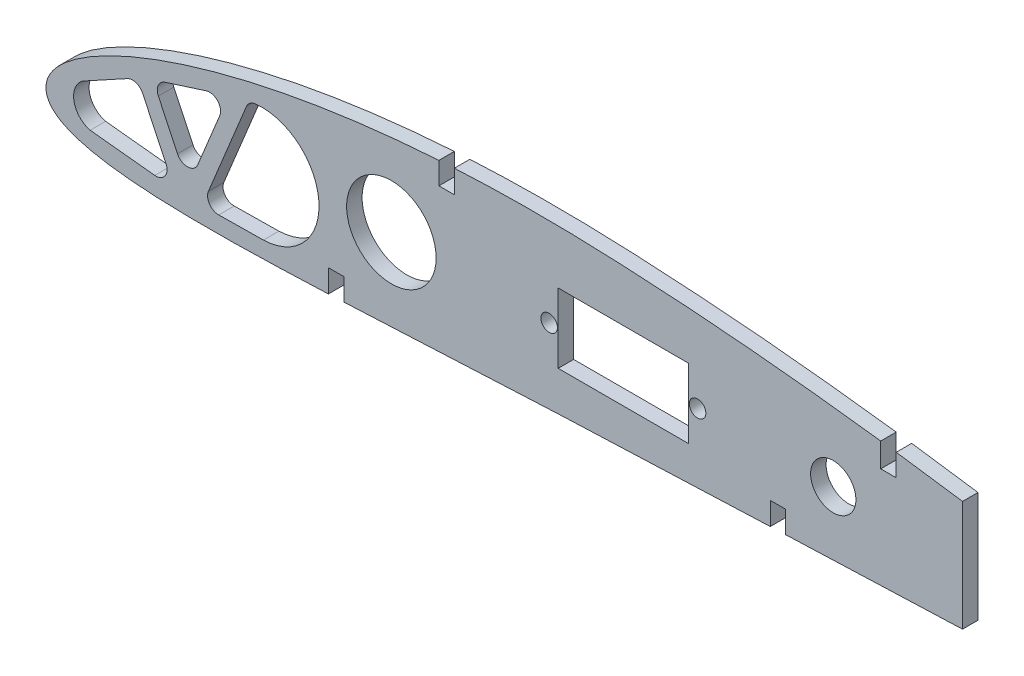
SolidWorks part; units mm, degrees
material "фанера"
ref_plane "Front" through (0, 0, 0) normal (0, 0, 1) x (1, 0, 0)
ref_plane "Top" through (0, 0, 0) normal (0, 1, 0) x (1, 0, 0)
ref_plane "Right" through (0, 0, 0) normal (1, 0, 0) x (0, 0, -1)
curve "Кривая1"
  spline degree 3 poles (0.048, 0.6214, 0) (0.0227, 0.3735, 0) (-0.0278, -0.1225, 0) (0.078, -0.8844, 0) (0.3497, -1.6388, 0) (0.8143, -2.3651, 0) (1.4635, -3.0393, 0) (2.291, -3.661, 0) (3.3059, -4.2358, 0) (4.5353, -4.7737, 0) (6.0297, -5.2822, 0) (7.869, -5.7653, 0) (10.1688, -6.2217, 0) (13.0754, -6.6396, 0) (16.7281, -6.993, 0) (21.19, -7.2473, 0) (26.4, -7.3766, 0) (32.1974, -7.3763, 0) (38.3978, -7.2614, 0) (44.8576, -7.0566, 0) (51.4865, -6.7865, 0) (58.231, -6.4723, 0) (65.0521, -6.1329, 0) (71.9108, -5.784, 0) (78.7714, -5.4397, 0) (85.6105, -5.111, 0) (92.4321, -4.805, 0) (99.255, -4.532, 0) (106.0974, -4.2783, 0) (112.9692, -4.0031, 0) (119.8644, -3.7232, 0) (126.7739, -3.4401, 0) (133.6816, -3.1587, 0) (140.5819, -2.8824, 0) (147.472, -2.6139, 0) (154.3526, -2.3556, 0) (161.225, -2.1094, 0) (168.0909, -1.8766, 0) (174.9516, -1.6586, 0) (181.8086, -1.4564, 0) (188.6632, -1.2704, 0) (195.5166, -1.1011, 0) (202.3695, -0.9486, 0) (209.2212, -0.8129, 0) (216.0668, -0.6936, 0) (222.8864, -0.5903, 0) (229.6176, -0.5029, 0) (236.0874, -0.4315, 0) (241.9808, -0.3765, 0) (246.559, -0.3395, 0) (249.1205, -0.3213, 0) (250, -0.315, 0) knots 0 0 0 0 0.002941 0.005884 0.009016 0.012365 0.016008 0.020037 0.024574 0.029784 0.035897 0.04324 0.052276 0.063635 0.077983 0.095698 0.11652 0.139661 0.164312 0.189919 0.216157 0.242838 0.269834 0.296993 0.324123 0.351139 0.378036 0.404946 0.431961 0.459078 0.486347 0.513641 0.540929 0.568176 0.59538 0.622543 0.649673 0.676775 0.703855 0.730919 0.757971 0.785018 0.812062 0.839103 0.866132 0.893099 0.919831 0.94581 0.969681 0.98959 1 1 1 1
curve "Кривая2"
  spline degree 3 poles (250, 0.315, 0) (249.1557, 0.545, 0) (246.7202, 1.2085, 0) (242.3913, 2.3583, 0) (236.8498, 3.7876, 0) (230.7799, 5.298, 0) (224.4559, 6.8129, 0) (218.0305, 8.2916, 0) (211.5624, 9.7197, 0) (205.0724, 11.0924, 0) (198.568, 12.4079, 0) (192.0524, 13.6653, 0) (185.5276, 14.8641, 0) (178.9953, 16.0034, 0) (172.4571, 17.0824, 0) (165.9143, 18.0998, 0) (159.3687, 19.0545, 0) (152.8218, 19.9449, 0) (146.2754, 20.7693, 0) (139.7314, 21.5257, 0) (133.1918, 22.212, 0) (126.6587, 22.8257, 0) (120.1368, 23.364, 0) (113.6286, 23.8247, 0) (107.1527, 24.2002, 0) (100.7411, 24.4984, 0) (94.4118, 24.6866, 0) (88.1559, 24.7401, 0) (81.949, 24.6588, 0) (75.7805, 24.441, 0) (69.6537, 24.0819, 0) (63.5754, 23.578, 0) (57.5552, 22.9249, 0) (51.6058, 22.1191, 0) (45.7444, 21.1566, 0) (39.9959, 20.0354, 0) (34.3979, 18.7563, 0) (29.0104, 17.3276, 0) (23.9258, 15.7719, 0) (19.2707, 14.1343, 0) (15.1791, 12.4833, 0) (11.7405, 10.8956, 0) (8.9594, 9.4296, 0) (6.7609, 8.1086, 0) (5.0337, 6.9246, 0) (3.6717, 5.8542, 0) (2.5921, 4.8713, 0) (1.7382, 3.9526, 0) (1.0699, 3.0809, 0) (0.5716, 2.2416, 0) (0.2158, 1.4308, 0) (0.1023, 0.8832, 0) (0.048, 0.6214, 0) knots 0 0 0 0 0.010162 0.029313 0.052012 0.076619 0.101948 0.127526 0.153184 0.178868 0.204558 0.230246 0.255926 0.281594 0.307246 0.332878 0.358485 0.384061 0.409603 0.435104 0.460559 0.485959 0.511303 0.536552 0.561723 0.586629 0.611085 0.635251 0.659272 0.683164 0.706922 0.730536 0.753983 0.777235 0.800246 0.822951 0.845237 0.866916 0.887662 0.906968 0.924203 0.938879 0.950932 0.960693 0.968647 0.975233 0.980795 0.985584 0.989782 0.993521 0.996902 1 1 1 1
sketch "Эскиз2" plane through (0, 0, 0) normal (0, 0, 1) x (1, 0, 0)
  line L0 (-1.2592, 0) -> (250.7702, 0) construction
  line L1 (250.1305, 0) -> (250.1305, 80.0888) construction
  line L2 (0, 0) -> (0, 69.7453) construction
  line L3 (62.5326, 123.1249) -> (62.5326, -48.5934) construction
  line L4 (142.5326, 131.1199) -> (142.5326, -55.0117) construction
  line L5 (62.5326, 8.5923) -> (142.5326, 8.6947) construction
  line L6 (62.5326, 8.5923) -> (150.6431, 8.5923) construction
  line L7 (175.0913, 92.567) -> (175.0913, -39.4544) construction
  line L8 (165.9405, 18.0854) -> (165.9405, -1.9504)
  line L18 (17.4887, 7.868) -> (21.7254, -1.0733)
  line L19 (29.4016, -1.5679) -> (36.2887, 15.1777)
  line L20 (20.3422, 8.8519) -> (23.813, 1.5271)
  line L21 (27.4701, 1.6228) -> (31.461, 11.3265)
  line L22 (7.9994, -2.6904) -> (19.7094, -3.9188)
  line L23 (31.2779, -4.3285) -> (39.3668, -4.221)
  line L24 (6.5801, 4.311) -> (14.7212, 8.7661)
  line L25 (21.5421, 11.6138) -> (29.0038, 13.9928)
  line L26 (72.5326, 27.406) -> (72.5326, 20.4403) construction
  line L27 (52.5326, -12.1202) -> (52.5326, -2.6904) construction
  line L28 (152.5326, 24.4982) -> (152.5326, 15.921) construction
  line L29 (132.5326, -7.5811) -> (132.5326, 3.1811) construction
  line L30 (151.1326, 20.1529) -> (151.1326, 15.7875)
  line L31 (151.1326, 15.7875) -> (153.9326, 15.7875)
  line L32 (153.9326, 15.7875) -> (153.9326, 19.7875)
  line L33 (131.1326, -3.2627) -> (131.1326, 0.8506)
  line L34 (131.1326, 0.8506) -> (133.9326, 0.8506)
  line L35 (133.9326, 0.8506) -> (133.9326, -3.1494)
  line L36 (71.1326, 24.1575) -> (71.1326, 20.1575)
  line L37 (71.1326, 20.1575) -> (73.9326, 20.1575)
  line L38 (73.9326, 20.1575) -> (73.9326, 24.3239)
  line L39 (51.1326, -6.7954) -> (51.1326, -2.6707)
  line L40 (51.1326, -2.6707) -> (53.9326, -2.6707)
  line L41 (53.9326, -2.6707) -> (53.9326, -6.6707)
  line L42 (116.3326, 14.946) -> (119.6026, 14.946) construction
  line L43 (92.7326, 2.346) -> (116.3326, 2.346)
  line L44 (92.7326, 2.346) -> (92.7326, 14.946)
  line L45 (92.7326, 14.946) -> (116.3326, 14.946)
  line L46 (116.3326, 2.346) -> (116.3326, 14.946)
  line L47 (92.7326, 2.346) -> (116.3326, 14.946) construction
  line L48 (92.7326, 14.946) -> (116.3326, 2.346) construction
  line L49 (119.6026, 14.946) -> (119.6026, 2.346) construction
  line L50 (119.6026, 2.346) -> (116.3326, 2.346) construction
  line L51 (104.5326, 11.3265) -> (104.5326, 5.8512) construction
  arc A0 (250, 0.315) -> (250, -0.315) centre (249.685, 0) cw
  circle A3 centre (62.5326, 8.5923) radius 8.1
  circle A5 centre (62.5326, 8.5923) radius 80 construction
  circle A6 centre (142.5326, 8.6947) radius 4.1
  arc A7 (175.0913, 16.6448) -> (175.0913, -1.657) centre (175.0913, 7.4939) ccw
  arc A16 (37.9117, 16.4041) -> (36.2887, 15.1777) centre (38.1384, 14.417) ccw
  arc A20 (6.5801, 4.311) -> (7.9994, -2.6904) centre (8.9558, 1.1481) ccw
  arc A21 (37.9117, 16.4041) -> (39.3668, -4.221) centre (39.0848, 6.123) cw
  arc A22 (23.813, 1.5271) -> (27.4701, 1.6228) centre (25.6204, 2.3835) ccw
  arc A23 (31.461, 11.3265) -> (29.0038, 13.9928) centre (29.6113, 12.0873) ccw
  arc A24 (20.3422, 8.8519) -> (21.5421, 11.6138) centre (22.1496, 9.7083) cw
  arc A25 (17.4887, 7.868) -> (14.7212, 8.7661) centre (15.6813, 7.0116) ccw
  arc A26 (19.7094, -3.9188) -> (21.7254, -1.0733) centre (19.9181, -1.9297) ccw
  arc A27 (29.4016, -1.5679) -> (31.2779, -4.3285) centre (31.2513, -2.3286) ccw
  circle A28 centre (175.0913, 7.4939) radius 1
  circle A29 centre (117.9676, 8.6632) radius 1.5
  circle A30 centre (91.0976, 8.6632) radius 1.5
  spline S0 degree 3 poles (250, 0.315) (249.1557, 0.545) (246.7202, 1.2085) (242.3913, 2.3583) (236.8498, 3.7876) (230.7799, 5.298) (224.4559, 6.8129) (218.0305, 8.2916) (211.5624, 9.7197) (205.0724, 11.0924) (198.568, 12.4079) (192.0524, 13.6653) (185.5276, 14.8641) (178.9953, 16.0034) (172.4571, 17.0824) (165.9143, 18.0998) (159.3687, 19.0545) (152.8218, 19.9449) (146.2754, 20.7693) (139.7314, 21.5257) (133.1918, 22.212) (126.6587, 22.8257) (120.1368, 23.364) (113.6286, 23.8247) (107.1527, 24.2002) (100.7411, 24.4984) (94.4118, 24.6866) (88.1559, 24.7401) (81.949, 24.6588) (75.7805, 24.441) (69.6537, 24.0819) (63.5754, 23.578) (57.5552, 22.9249) (51.6058, 22.1191) (45.7444, 21.1566) (39.9959, 20.0354) (34.3979, 18.7563) (29.0104, 17.3276) (23.9258, 15.7719) (19.2707, 14.1343) (15.1791, 12.4833) (11.7405, 10.8956) (8.9594, 9.4296) (6.7609, 8.1086) (5.0337, 6.9246) (3.6717, 5.8542) (2.5921, 4.8713) (1.7382, 3.9526) (1.0699, 3.0809) (0.5716, 2.2416) (0.2158, 1.4308) (0.1023, 0.8832) (0.048, 0.6214) knots 0 0 0 0 0.010162 0.029313 0.052012 0.076619 0.101948 0.127526 0.153184 0.178868 0.204558 0.230246 0.255926 0.281594 0.307246 0.332878 0.358485 0.384061 0.409603 0.435104 0.460559 0.485959 0.511303 0.536552 0.561723 0.586629 0.611085 0.635251 0.659272 0.683164 0.706922 0.730536 0.753983 0.777235 0.800246 0.822951 0.845237 0.866916 0.887662 0.906968 0.924203 0.938879 0.950932 0.960693 0.968647 0.975233 0.980795 0.985584 0.989782 0.993521 0.996902 1 1 1 1 construction
  spline S1 degree 3 poles (0.048, 0.6214) (0.0227, 0.3735) (-0.0278, -0.1225) (0.078, -0.8844) (0.3497, -1.6388) (0.8143, -2.3651) (1.4635, -3.0393) (2.291, -3.661) (3.3059, -4.2358) (4.5353, -4.7737) (6.0297, -5.2822) (7.869, -5.7653) (10.1688, -6.2217) (13.0754, -6.6396) (16.7281, -6.993) (21.19, -7.2473) (26.4, -7.3766) (32.1974, -7.3763) (38.3978, -7.2614) (44.8576, -7.0566) (51.4865, -6.7865) (58.231, -6.4723) (65.0521, -6.1329) (71.9108, -5.784) (78.7714, -5.4397) (85.6105, -5.111) (92.4321, -4.805) (99.255, -4.532) (106.0974, -4.2783) (112.9692, -4.0031) (119.8644, -3.7232) (126.7739, -3.4401) (133.6816, -3.1587) (140.5819, -2.8824) (147.472, -2.6139) (154.3526, -2.3556) (161.225, -2.1094) (168.0909, -1.8766) (174.9516, -1.6586) (181.8086, -1.4564) (188.6632, -1.2704) (195.5166, -1.1011) (202.3695, -0.9486) (211.4992, -0.7677) (220.6031, -0.6199) (229.6176, -0.5029) (236.0874, -0.4315) (241.9808, -0.3765) (246.559, -0.3395) (249.1205, -0.3213) (250, -0.315) knots 0 0 0 0 0.002941 0.005884 0.009016 0.012365 0.016008 0.020037 0.024574 0.029784 0.035897 0.04324 0.052276 0.063635 0.077983 0.095698 0.11652 0.139661 0.164312 0.189919 0.216157 0.242838 0.269834 0.296993 0.324123 0.351139 0.378036 0.404946 0.431961 0.459078 0.486347 0.513641 0.540929 0.568176 0.59538 0.622543 0.649673 0.676775 0.703855 0.730919 0.757971 0.785018 0.812062 0.839103 0.893099 0.919831 0.94581 0.969681 0.98959 1 1 1 1 construction
  spline S2 degree 3 poles (250, 0.315) (249.1557, 0.545) (246.7202, 1.2085) (242.3913, 2.3583) (236.8498, 3.7876) (230.7799, 5.298) (224.4559, 6.8129) (218.0305, 8.2916) (211.5624, 9.7197) (205.0724, 11.0924) (198.568, 12.4079) (192.0524, 13.6653) (185.5276, 14.8641) (178.9953, 16.0034) (172.4571, 17.0824) (165.9143, 18.0998) (159.7397, 19.0004) (155.7443, 19.5471) (153.9326, 19.7875) knots 0 0 0 0 0.010162 0.029313 0.052012 0.076619 0.101948 0.127526 0.153184 0.178868 0.204558 0.230246 0.255926 0.281594 0.307246 0.332878 0.358485 0.379707 0.379707 0.379707 0.379707
  spline S3 degree 3 poles (0.048, 0.6214) (0.0227, 0.3735) (-0.0278, -0.1225) (0.078, -0.8844) (0.3497, -1.6388) (0.8143, -2.3651) (1.4635, -3.0393) (2.291, -3.661) (3.3059, -4.2358) (4.5353, -4.7737) (6.0297, -5.2822) (7.869, -5.7653) (10.1688, -6.2217) (13.0754, -6.6396) (16.7281, -6.993) (21.19, -7.2473) (26.4, -7.3766) (32.1974, -7.3763) (38.3978, -7.2614) (44.7521, -7.06) (49.0233, -6.8868) (51.1326, -6.7954) knots 0 0 0 0 0.002941 0.005884 0.009016 0.012365 0.016008 0.020037 0.024574 0.029784 0.035897 0.04324 0.052276 0.063635 0.077983 0.095698 0.11652 0.139661 0.164312 0.189919 0.214908 0.214908 0.214908 0.214908
  spline S4 degree 3 poles (151.1326, 20.1529) (149.5127, 20.3609) (145.7129, 20.8343) (139.7314, 21.5257) (133.1918, 22.212) (126.6587, 22.8257) (120.1368, 23.364) (113.6286, 23.8247) (107.1527, 24.2002) (100.7411, 24.4984) (94.4118, 24.6866) (88.1559, 24.7401) (81.949, 24.6588) (77.2124, 24.4916) (74.545, 24.3569) (73.9326, 24.3239) knots 0.390637 0.390637 0.390637 0.390637 0.409603 0.435104 0.460559 0.485959 0.511303 0.536552 0.561723 0.586629 0.611085 0.635251 0.659272 0.683164 0.690286 0.690286 0.690286 0.690286
  spline S5 degree 3 poles (133.9326, -3.1494) (136.1503, -3.0598) (140.6644, -2.8792) (147.472, -2.6139) (154.3526, -2.3556) (161.225, -2.1094) (168.0909, -1.8766) (174.9516, -1.6586) (181.8086, -1.4564) (188.6632, -1.2704) (195.5166, -1.1011) (202.3695, -0.9486) (211.4992, -0.7677) (220.6031, -0.6199) (229.6176, -0.5029) (236.0874, -0.4315) (241.9808, -0.3765) (246.559, -0.3395) (249.1205, -0.3213) (250, -0.315) knots 0.541906 0.541906 0.541906 0.541906 0.568176 0.59538 0.622543 0.649673 0.676775 0.703855 0.730919 0.757971 0.785018 0.812062 0.839103 0.893099 0.919831 0.94581 0.969681 0.98959 1 1 1 1
  spline S6 degree 3 poles (71.1326, 24.1575) (70.636, 24.1252) (68.1106, 23.954) (63.5754, 23.578) (57.5552, 22.9249) (51.6058, 22.1191) (45.7444, 21.1566) (39.9959, 20.0354) (34.3979, 18.7563) (29.0104, 17.3276) (23.9258, 15.7719) (19.2707, 14.1343) (15.1791, 12.4833) (11.7405, 10.8956) (8.9594, 9.4296) (6.7609, 8.1086) (5.0337, 6.9246) (3.6717, 5.8542) (2.5921, 4.8713) (1.7382, 3.9526) (1.0699, 3.0809) (0.5716, 2.2416) (0.2158, 1.4308) (0.1023, 0.8832) (0.048, 0.6214) knots 0.701143 0.701143 0.701143 0.701143 0.706922 0.730536 0.753983 0.777235 0.800246 0.822951 0.845237 0.866916 0.887662 0.906968 0.924203 0.938879 0.950932 0.960693 0.968647 0.975233 0.980795 0.985584 0.989782 0.993521 0.996902 1 1 1 1
  spline S7 degree 3 poles (53.9326, -6.6707) (55.3566, -6.6057) (59.0587, -6.4311) (65.0521, -6.1329) (71.9108, -5.784) (78.7714, -5.4397) (85.6105, -5.111) (92.4321, -4.805) (99.255, -4.532) (106.0974, -4.2783) (112.9692, -4.0031) (119.8644, -3.7232) (125.9231, -3.4749) (129.6799, -3.3217) (131.1326, -3.2627) knots 0.225966 0.225966 0.225966 0.225966 0.242838 0.269834 0.296993 0.324123 0.351139 0.378036 0.404946 0.431961 0.459078 0.486347 0.513641 0.53085 0.53085 0.53085 0.53085
  point P15 (62.5326, 0)
  point P16 (142.5326, 0)
  point P22 (62.5326, -6.2577)
  point P26 (175.0913, 16.6448)
  point P28 (175.0913, -1.657)
  point P34 (104.5326, 8.646)
  point P48 (117.9676, 14.946)
  point P50 (62.5326, 23.4501)
  point P86 (25.7497, -2.5601)
  point P88 (23.2497, -4.2901)
  point P91 (28.2497, -4.3687)
  dimension "D6" = 16.2
  dimension "D7" = 160
  dimension "D9" = 8.2
  dimension "D12" = 9.1509
  dimension "D29" = 2
  dimension "D14" = 2
  dimension "D30" = 2
  dimension "D17" = 3
  dimension "D2" = 250.1305
  dimension "D4" = 80
  dimension "D11" = 175.0913
  dimension "D13" = 67.8
  dimension "D20" = 5
  dimension "D24" = 5
  dimension "D25" = 3
  dimension "D26" = 3
  dimension "D27" = 5
  dimension "D28" = 2.5
  dimension "D31" = 10
  dimension "D32" = 10
  dimension "D33" = 10
  dimension "D34" = 10
  dimension "D35" = 2.8
  dimension "D36" = 1.4
  dimension "D37" = 4
  dimension "D38" = 2.8
  dimension "D39" = 1.4
  dimension "D40" = 4
  dimension "D42" = 1.4
  dimension "D43" = 4
  dimension "D44" = 1.4
  dimension "D45" = 2.8
  dimension "D46" = 4
  dimension "D15" = 23.6
  dimension "D16" = 12.6
  dimension "D5" = 29.7079
  dimension "D8" = 33.9
  dimension "D10" = 3.27
extrude "Бобышка-Вытянуть2" add sketch "Эскиз2" along normal mid plane 2.8
equation "\"D7@Эскиз2\"=\"D4@Эскиз2\"*2"
equation "\"D11@Эскиз2\"=\"D2@Эскиз2\"*0.7"
equation "\"D28@Эскиз2\"=\"D27@Эскиз2\"/2"
equation "\"D8@Эскиз2\"=\"D13@Эскиз2\"/2"
